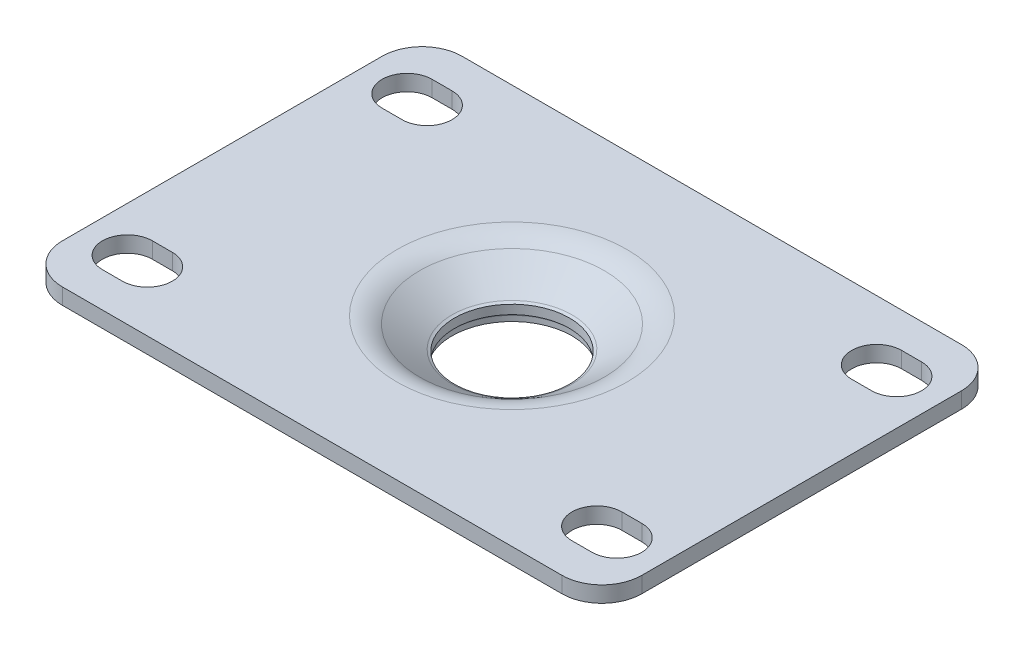
SolidWorks part; units mm, degrees
ref_plane "Front Plane" through (0, 0, 0) normal (0, 0, 1) x (1, 0, 0)
ref_plane "Top Plane" through (0, 0, 0) normal (0, 1, 0) x (1, 0, 0)
ref_plane "Right Plane" through (0, 0, 0) normal (1, 0, 0) x (0, 0, -1)
sketch "Sk_pressed_centre" plane through (0, 0, 0) normal (0, 0, 1) x (1, 0, 0)
  line L0 (19.304, 69.85) -> (18.2626, 69.85)
  line L1 (14.6695, 68.7349) -> (9.5402, 65.2145)
  line L2 (9.1313, 64.9884) -> (9.1313, 63.5508)
  line L3 (9.1313, 63.5508) -> (9.1567, 63.5508)
  line L4 (9.5377, 63.1698) -> (9.5377, 62.3138)
  line L5 (10.3276, 62.6745) -> (15.4572, 66.1949)
  line L6 (19.05, 67.31) -> (19.304, 67.31)
  line L7 (19.304, 67.31) -> (19.304, 69.85)
  line L8 (0, -25.4) -> (0, 76.2) construction
  arc A0 (18.2626, 69.85) -> (14.6695, 68.7349) centre (18.2616, 63.5067) ccw
  arc A1 (9.5402, 65.2145) -> (9.1313, 64.9884) centre (8.2156, 67.1279) cw
  arc A2 (9.1567, 63.5508) -> (9.5377, 63.1698) centre (9.1567, 63.1698) cw
  arc A3 (9.5377, 62.3138) -> (10.3276, 62.6745) centre (8.8772, 64.8059) ccw
  arc A4 (15.4572, 66.1949) -> (19.05, 67.31) centre (19.0537, 60.9524) cw
revolve "Rev_pressed_centre" add sketch "Sk_pressed_centre" angle 360 about L8
ref_plane "Plane_plate_bottom" through (0, 67.31, 0) normal (0, 1, 0) x (1, 0, 0)
sketch "Sk_plate_outline_slots" plane through (0, 67.31, 0) normal (0, 1, 0) x (1, 0, 0)
  line L0 (-39.6875, 31.75) -> (39.6875, 31.75)
  line L1 (46.0375, 25.4) -> (46.0375, -25.4)
  line L2 (39.6875, -31.75) -> (-39.6875, -31.75)
  line L3 (-46.0375, -25.4) -> (-46.0375, 25.4)
  line L4 (-38.8937, 26.1937) -> (-35.7188, 26.1937)
  line L5 (-35.7188, 18.2562) -> (-38.8937, 18.2562)
  line L6 (-38.8937, -18.2562) -> (-35.7188, -18.2562)
  line L7 (-35.7188, -26.1937) -> (-38.8937, -26.1937)
  line L8 (35.7188, 26.1937) -> (38.8937, 26.1937)
  line L9 (38.8937, 18.2562) -> (35.7188, 18.2562)
  line L10 (35.7188, -18.2562) -> (38.8937, -18.2562)
  line L11 (38.8937, -26.1937) -> (35.7188, -26.1937)
  arc A0 (39.6875, 31.75) -> (46.0375, 25.4) centre (39.6875, 25.4) cw
  arc A1 (46.0375, -25.4) -> (39.6875, -31.75) centre (39.6875, -25.4) cw
  arc A2 (-39.6875, -31.75) -> (-46.0375, -25.4) centre (-39.6875, -25.4) cw
  arc A3 (-46.0375, 25.4) -> (-39.6875, 31.75) centre (-39.6875, 25.4) cw
  arc A4 (-35.7188, 26.1937) -> (-35.7188, 18.2562) centre (-35.7187, 22.225) cw
  arc A5 (-38.8937, 18.2562) -> (-38.8937, 26.1937) centre (-38.8938, 22.225) cw
  arc A6 (-35.7188, -18.2562) -> (-35.7188, -26.1937) centre (-35.7187, -22.225) cw
  arc A7 (-38.8937, -26.1937) -> (-38.8937, -18.2562) centre (-38.8938, -22.225) cw
  arc A8 (38.8937, 26.1937) -> (38.8937, 18.2562) centre (38.8938, 22.225) cw
  arc A9 (35.7188, 18.2562) -> (35.7188, 26.1937) centre (35.7187, 22.225) cw
  arc A10 (38.8937, -18.2562) -> (38.8937, -26.1937) centre (38.8938, -22.225) cw
  arc A11 (35.7188, -26.1937) -> (35.7188, -18.2562) centre (35.7187, -22.225) cw
  circle A12 centre (0, 0) radius 19.05
extrude "Ext_plate" add sketch "Sk_plate_outline_slots" along normal blind 2.54
